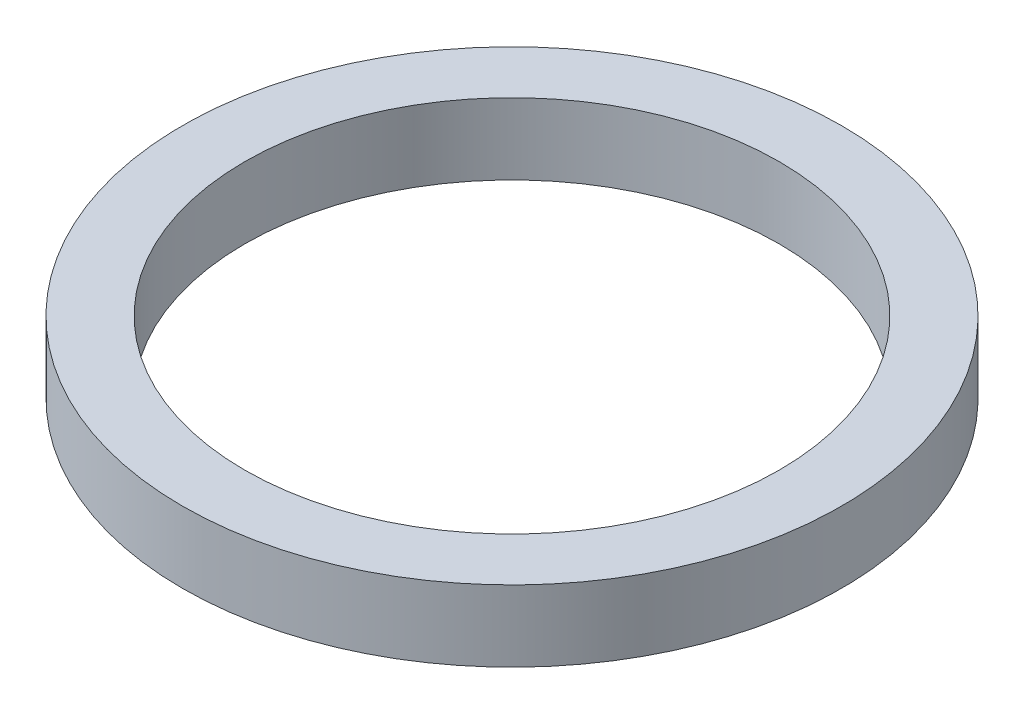
SolidWorks part; units mm, degrees
ref_plane "Front Plane" through (0, 0, 0) normal (0, 0, 1) x (1, 0, 0)
ref_plane "Top Plane" through (0, 0, 0) normal (0, 1, 0) x (1, 0, 0)
ref_plane "Right Plane" through (0, 0, 0) normal (1, 0, 0) x (0, 0, -1)
other "Bounding Box"
ref_plane "Default Plane" through (-8.9266, -12.7485, 0) normal (-0.1736, 0.9848, 0) x (0.9848, 0.1736, 0)
sketch "Sketch1" plane through (0, 0, 0) normal (0, 1, 0) x (1, 0, 0)
  circle A0 centre (0, 0) radius 18.5
  circle A1 centre (0, 0) radius 15
  dimension "D1" = 37
  dimension "D2" = 30
extrude "Boss-Extrude1" add sketch "Sketch1" along normal mid plane 4
